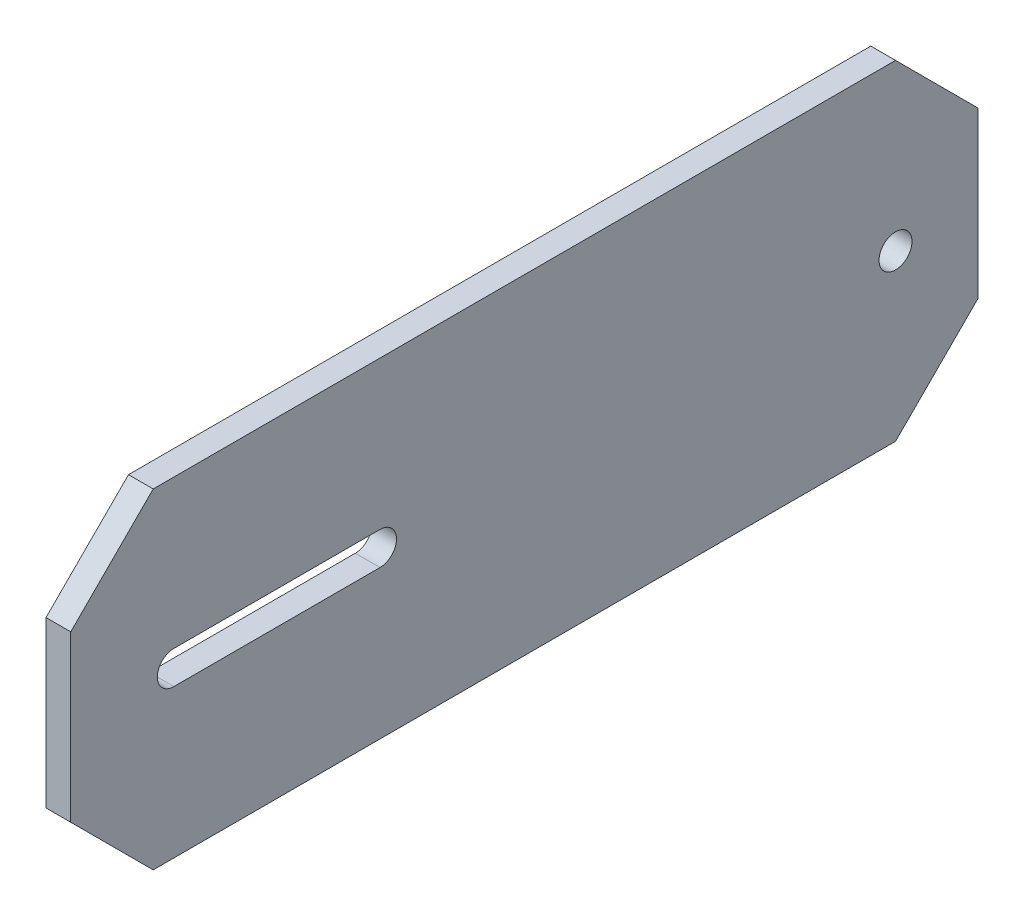
SolidWorks part; units mm, degrees
ref_plane "Alzado" through (0, 0, 0) normal (0, 0, 1) x (1, 0, 0)
ref_plane "Planta" through (0, 0, 0) normal (0, 1, 0) x (1, 0, 0)
ref_plane "Vista lateral" through (0, 0, 0) normal (1, 0, 0) x (0, 0, -1)
sketch "Croquis2" plane through (0, 0, 0) normal (1, 0, 0) x (0, 0, -1)
  line L0 (0, 0) -> (90, 0)
  line L1 (90, 0) -> (100, 10)
  line L2 (100, 10) -> (100, 30)
  line L3 (100, 30) -> (90, 40)
  line L4 (90, 40) -> (0, 40)
  line L5 (0, 40) -> (-10, 30)
  line L6 (-10, 30) -> (-10, 10)
  line L7 (-10, 10) -> (0, 0)
  dimension "D1" = 135
  dimension "D2" = 90
  dimension "D3" = 40
  dimension "D4" = 20
  dimension "D5" = 135
extrude "Saliente-Extruir1" add sketch "Croquis2" along normal blind 3
sketch "Croquis3" plane through (3, 0, 0) normal (1, 0, 0) x (0, 0, -1)
  line L0 (-10, 20) -> (100, 20) construction
  line L1 (-10, 30) -> (-10, 10) construction
  line L2 (100, 10) -> (100, 30) construction
  line L3 (2.5, 22) -> (27.5, 22)
  line L4 (2.5, 18) -> (27.5, 18)
  line L5 (0.5, 20) -> (29.5, 20) construction
  line L6 (15, 18) -> (15, 22) construction
  circle A0 centre (90, 20) radius 2
  arc A1 (27.5, 22) -> (27.5, 18) centre (27.5, 20) cw
  arc A2 (2.5, 18) -> (2.5, 22) centre (2.5, 20) cw
  point P16 (15, 20)
  dimension "D3" = 4
  dimension "D1" = 25
  dimension "D2" = 25
  dimension "D4" = 10
  dimension "D5" = 4
extrude "Cortar-Extruir1" cut sketch "Croquis3" against normal blind 9
